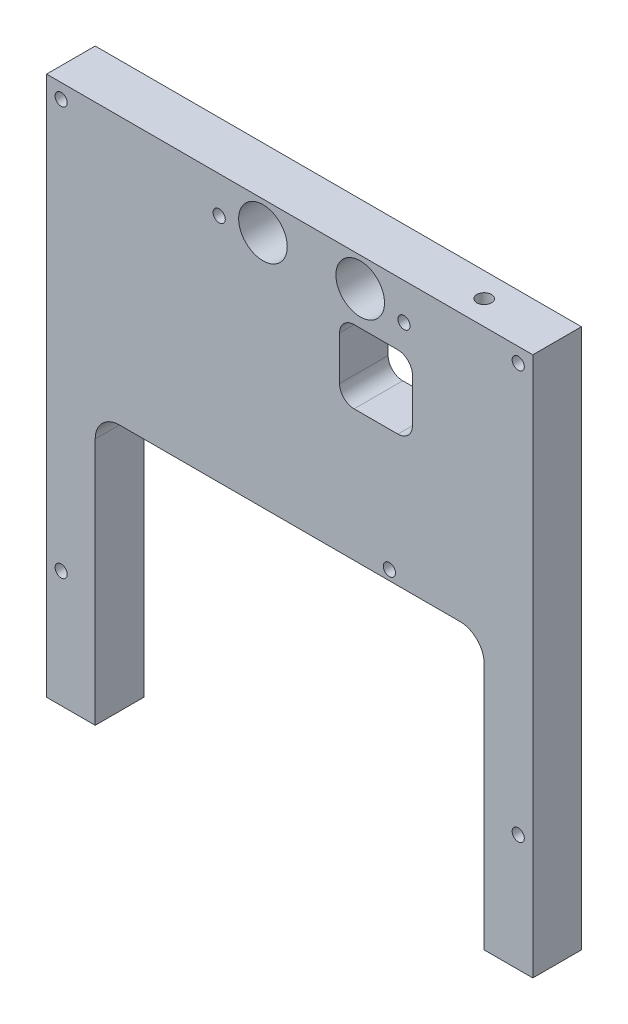
SolidWorks part; units mm, degrees
material "Alliage 1060"
ref_plane "Plan de face" through (0, 0, 0) normal (0, 0, 1) x (1, 0, 0)
ref_plane "Plan de dessus" through (0, 0, 0) normal (0, 1, 0) x (1, 0, 0)
ref_plane "Plan de droite" through (0, 0, 0) normal (1, 0, 0) x (0, 0, -1)
sketch "Esquisse1" plane through (0, 0, 0) normal (0, 0, 1) x (1, 0, 0)
  line L0 (-40, 9) -> (-50, 9)
  line L1 (-50, 9) -> (-50, 120)
  line L2 (-50, 120) -> (50, 120)
  line L3 (50, 120) -> (50, 9)
  line L4 (50, 9) -> (40, 9)
  line L5 (40, 9) -> (40, 60)
  line L7 (-40, 60) -> (-40, 9)
  line L8 (0, 0) -> (0, 105.6623) construction
  line L11 (39, 20) -> (39, 21.6) construction
  line L14 (35, 65) -> (-35, 65)
  arc A0 (40, 60) -> (35, 65) centre (35, 60) ccw
  arc A1 (-35, 65) -> (-40, 60) centre (-35, 60) ccw
  dimension "D5" = 5
  dimension "D1" = 111
  dimension "D2" = 1
  dimension "D3" = 120
  dimension "D4" = 10
extrude "Extrusion1" add sketch "Esquisse1" along normal blind 10
hole_wizard "Trou taraudé M4x0.71" positions "Esquisse3" profile "Esquisse2" tap size "M4x0.7" standard "ISO"
sketch "Esquisse3" plane through (0, 9, 0) normal (0, -1, 0) x (1, 0, 0)
  line L0 (50, 0) -> (40, 10) construction
  line L2 (-40, 10) -> (-50, 0) construction
  point P0 (-45, 5)
  point P1 (45, 5)
sketch "Esquisse2" plane through (-45, 9, 5) normal (1, 0, 0) x (0, 0, -1)
  line L0 (0, 0) -> (0, 15.9914)
  line L1 (0, 15.9914) -> (1.65, 15)
  line L2 (1.65, 15) -> (1.65, 0)
  line L5 (1.65, 0) -> (0, 0)
  line L10 (0, 15.9914) -> (-1.65, 15) construction
  line L11 (0, -6.35) -> (0, 107.95) construction
  dimension "Diamètre du trou pour taraudage" = 3.3
  dimension "Profondeur du trou pour taraudage" = 15
  dimension "Angle de pointe" = 118
cosmetic thread "Filetage de perçage1" parameters "D1"=8, "D2"=4
cosmetic thread "Filetage de perçage2" parameters "D1"=8, "D2"=4
sketch "Esquisse4" plane through (0, 0, 0) normal (0, 0, 1) x (1, 0, 0)
  line L1 (22.25, 107) -> (13.25, 107)
  line L2 (25.25, 104) -> (25.25, 95)
  line L3 (22.25, 92) -> (13.25, 92)
  line L4 (10.25, 104) -> (10.25, 95)
  circle A12 centre (14.5, 114) radius 5
  circle A13 centre (-5.5, 114) radius 5
  arc A16 (22.25, 107) -> (25.25, 104) centre (22.25, 104) cw
  arc A17 (13.25, 107) -> (10.25, 104) centre (13.25, 104) ccw
  arc A18 (13.25, 92) -> (10.25, 95) centre (13.25, 95) cw
  arc A19 (25.25, 95) -> (22.25, 92) centre (22.25, 95) cw
extrude "Enlèv. mat.-Extru.1" cut sketch "Esquisse4" along normal through all
hole_wizard "Trou taraudé M31" positions "Esquisse6" profile "Esquisse5" tap size "M3" standard "ISO" end condition through all
sketch "Esquisse6" plane through (0, 0, 0) normal (0, 0, -1) x (-1, 0, 0)
  point P0 (-23.5, 112.5)
  point P1 (14.5, 112.5)
  point P2 (-20.5, 67)
  point P3 (-47, 117)
  point P4 (47, 117)
  point P5 (47, 33)
  point P6 (-47, 33)
sketch "Esquisse5" plane through (23.5, 112.5, 0) normal (1, 0, 0) x (0, 1, 0)
  line L0 (0, 0) -> (0, 10)
  line L1 (0, 10) -> (1.25, 10)
  line L2 (1.25, 10) -> (1.25, 0)
  line L5 (1.25, 0) -> (0, 0)
  line L11 (0, -6.35) -> (0, 107.95) construction
  dimension "Diamètre du trou pour taraudage jusqu'au prochain" = 2.5
  dimension "Profondeur du trou pour taraudage jusqu'au prochain" = 10
cosmetic thread "Filetage de perçage3" parameters "D2"=3
cosmetic thread "Filetage de perçage4" parameters "D2"=3
cosmetic thread "Filetage de perçage5" parameters "D2"=3
cosmetic thread "Filetage de perçage6" parameters "D2"=3
cosmetic thread "Filetage de perçage7" parameters "D2"=3
cosmetic thread "Filetage de perçage8" parameters "D2"=3
cosmetic thread "Filetage de perçage9" parameters "D2"=3
sketch "Esquisse7" plane through (0, 120, 0) normal (0, 1, 0) x (1, 0, 0)
  line L0 (35, 0) -> (35, -10) construction
  line L3 (50, 0) -> (-50, 0) construction
  line L5 (50, -10) -> (-50, -10) construction
  circle A0 centre (35, -5) radius 1.5
  point P6 (0, 0)
  dimension "D1" = 3
  dimension "D2" = 35
extrude "Enlèv. mat.-Extru.2" cut sketch "Esquisse7" against normal blind 10
